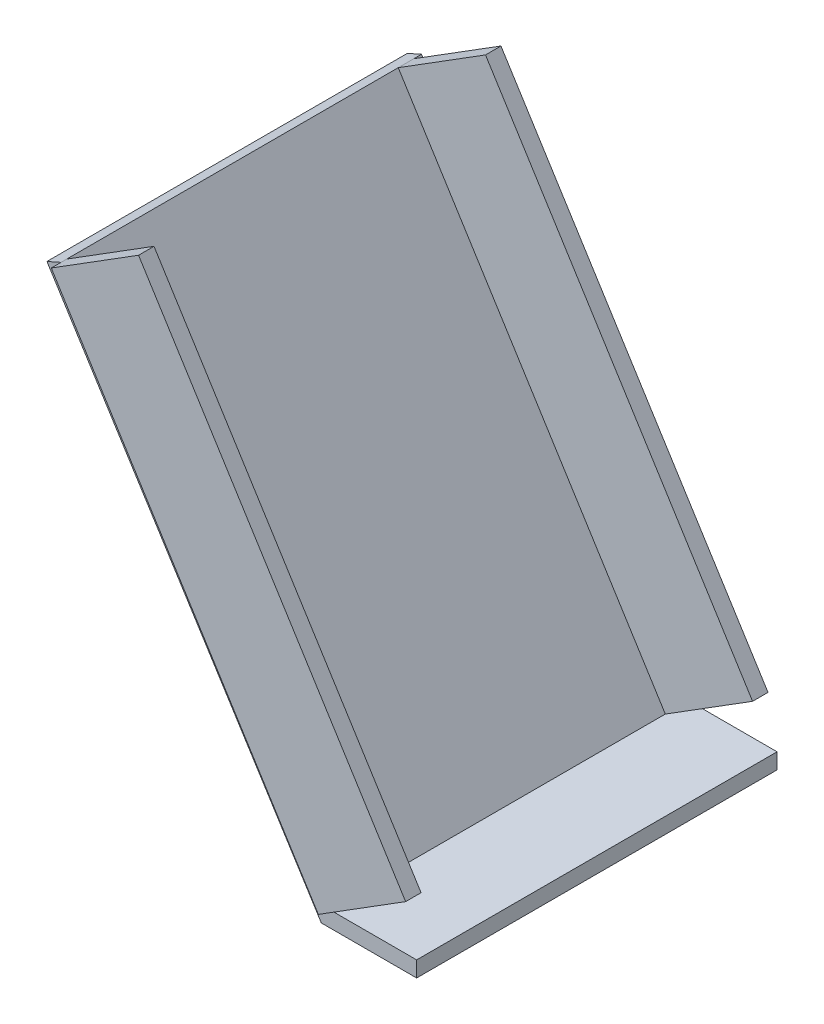
SolidWorks part; units mm, degrees
ref_plane "Front Plane" through (0, 0, 0) normal (0, 0, 1) x (1, 0, 0)
ref_plane "Top Plane" through (0, 0, 0) normal (0, 1, 0) x (1, 0, 0)
ref_plane "Right Plane" through (0, 0, 0) normal (1, 0, 0) x (0, 0, -1)
sketch "Sketch1" plane through (0, 0, 0) normal (0, 0, 1) x (1, 0, 0)
  line L0 (-26.6461, 42.3082) -> (26.6461, -42.3082)
  line L1 (-26.6461, 42.3082) -> (-23.9046, 43.5267)
  line L2 (-23.9046, 43.5267) -> (27.9637, -39.2592)
  line L3 (27.9637, -39.2592) -> (45.1559, -39.2592)
  line L4 (45.1559, -39.2592) -> (45.1559, -42.3082)
  line L5 (45.1559, -42.3082) -> (26.6461, -42.3082)
  point P4 (0, 0)
  dimension "D1" = 100
  dimension "D2" = 3
extrude "Boss-Extrude1" add sketch "Sketch1" along normal mid plane 70
sketch "Sketch3" plane through (2.4174, 1.5146, 0) normal (0.8474, 0.5309, 0) x (0, 0, -1)
  line L0 (-33.8958, 49.5768) -> (-33.8958, -48.1156)
  line L1 (-35, 49.5768) -> (35, 49.5768) construction
  line L2 (-35, -48.1156) -> (35, -48.1156) construction
  line L3 (33.4874, 49.5768) -> (33.4874, -48.1156)
extrude "Extrude-Thin1" add sketch "Sketch3" along normal blind 20 thin
